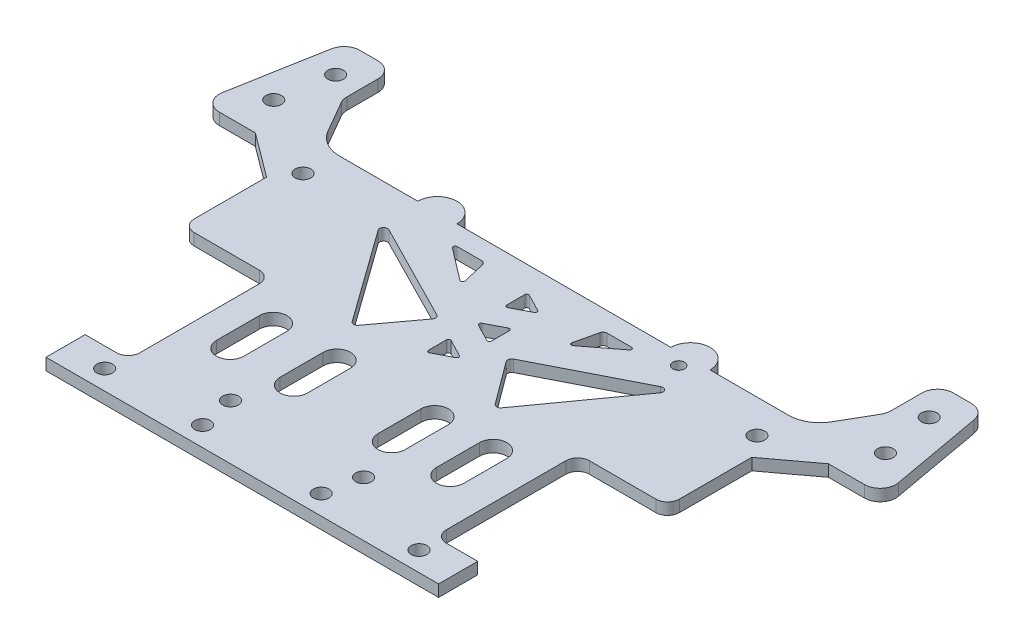
SolidWorks part; units mm, degrees
ref_plane "前视基准面" through (0, 0, 0) normal (0, 0, 1) x (1, 0, 0)
ref_plane "上视基准面" through (0, 0, 0) normal (0, 1, 0) x (1, 0, 0)
ref_plane "右视基准面" through (0, 0, 0) normal (1, 0, 0) x (0, 0, -1)
other "Configuration Table"
sketch "草图1" plane through (0, 0, 0) normal (0, 1, 0) x (1, 0, 0)
  line L0 (0, -104.2546) -> (0, 104.2546) construction
  point P3 (0, 0)
sketch "草图2" plane through (0, 0, 0) normal (0, 1, 0) x (1, 0, 0)
  line L0 (335.3431, 5) -> (-235.3431, 5) construction
  line L1 (-50, 0) -> (50, 0)
  line L2 (0, 0) -> (0, 19.5248) construction
  line L3 (42, 10) -> (50, 10)
  line L4 (50, 0) -> (50, 10)
  line L6 (0, 19.5248) -> (0, 40.19) construction
  line L8 (39, 13) -> (39, 43.53)
  line L9 (42, 46.53) -> (59, 46.53)
  line L10 (0, 40.19) -> (0, 82.03) construction
  line L11 (-57.3812, 82.03) -> (-37.34, 82.03)
  line L12 (62, 49.53) -> (62, 68.03)
  line L13 (64.3094, 86.03) -> (68.9641, 94.0922)
  line L14 (69.5, 96.0922) -> (69.5, 104.0204)
  line L17 (73.5, 108.0204) -> (78.1587, 108.0204)
  line L19 (82.0948, 104.7324) -> (86.3672, 81.1158)
  line L20 (62, 68.03) -> (73.2197, 76.4037)
  line L21 (73.2197, 76.4037) -> (82.4311, 76.4037)
  line L22 (12.5, 25.5) -> (12.5, 36.5) construction
  line L23 (9, 25.5) -> (9, 36.5)
  line L24 (16, 25.5) -> (16, 36.5)
  line L25 (-73.5, 108.0204) -> (-78.1587, 108.0204)
  line L26 (-69.5, 96.0922) -> (-69.5, 104.0204)
  line L27 (-64.3094, 86.03) -> (-68.9641, 94.0922)
  line L29 (-42.32, 10) -> (-50.32, 10)
  line L30 (-39.32, 13) -> (-39.32, 43.53)
  line L31 (-42.32, 46.53) -> (-59, 46.53)
  line L32 (-62, 49.53) -> (-62, 68.03)
  line L33 (-62, 68.03) -> (-73.2197, 76.4037)
  line L34 (-73.2197, 76.4037) -> (-82.4311, 76.4037)
  line L35 (-82.0948, 104.7324) -> (-86.3672, 81.1158)
  line L36 (-12.5, 25.5) -> (-12.5, 36.5) construction
  line L37 (-9, 25.5) -> (-9, 36.5)
  line L38 (-16, 25.5) -> (-16, 36.5)
  line L39 (-50.32, 10) -> (-50.32, 0)
  line L40 (-50, 0) -> (-50.32, 0)
  line L41 (-28.772, 36.5) -> (-28.772, 25.5) construction
  line L42 (-25.272, 36.5) -> (-25.272, 25.5)
  line L43 (-32.272, 36.5) -> (-32.272, 25.5)
  line L45 (27.4578, 36.5) -> (27.4578, 25.5) construction
  line L46 (30.9578, 36.5) -> (30.9578, 25.5)
  line L47 (23.9578, 36.5) -> (23.9578, 25.5)
  line L60 (-34.7339, 72.03) -> (-9.7834, 59.3228)
  line L61 (-9.4337, 57.8365) -> (-17.4687, 46.9881)
  line L62 (-19.0845, 47) -> (-36, 70.5556)
  line L63 (-22.2986, 77.03) -> (-15.9986, 77.03)
  line L64 (-15.0247, 76.2572) -> (-13.6616, 70.4141)
  line L65 (-14.4522, 69.9032) -> (-22.6022, 76.1328)
  line L66 (9.4337, 57.8365) -> (17.4687, 46.9881)
  line L67 (19.0845, 47) -> (36, 70.5556)
  line L68 (34.7339, 72.03) -> (9.7834, 59.3228)
  line L69 (14.4522, 69.9032) -> (22.6022, 76.1328)
  line L70 (15.0247, 76.2572) -> (13.6616, 70.4141)
  line L71 (22.2986, 77.03) -> (15.9986, 77.03)
  line L72 (-3.0133, 75.03) -> (-3.0133, 70.43)
  line L73 (-2.2833, 69.986) -> (2.1563, 72.286)
  line L74 (2.1563, 73.174) -> (-2.2833, 75.474)
  line L75 (3.0133, 65.0858) -> (3.0133, 60.4858)
  line L76 (2.2833, 60.0419) -> (-2.1563, 62.3419)
  line L77 (-2.1563, 63.2298) -> (2.2833, 65.5298)
  line L81 (-2.2833, 49.986) -> (2.1563, 52.286)
  line L82 (-3.0133, 55.03) -> (-3.0133, 50.43)
  line L83 (2.1563, 53.174) -> (-2.2833, 55.474)
  line L84 (32.34, 79) -> (32.34, 82.03) construction
  line L87 (-27.34, 82.03) -> (27.34, 82.03)
  line L88 (37.34, 82.03) -> (57.3812, 82.03)
  arc A0 (82.4311, 76.4037) -> (86.3672, 81.1158) centre (82.4311, 80.4037) ccw
  arc A1 (82.0948, 104.7324) -> (78.1587, 108.0204) centre (78.1587, 104.0204) ccw
  arc A2 (69.5, 104.0204) -> (73.5, 108.0204) centre (73.5, 104.0204) cw
  arc A3 (68.9641, 94.0922) -> (69.5, 96.0922) centre (65.5, 96.0922) ccw
  arc A4 (64.3094, 86.03) -> (57.3812, 82.03) centre (57.3812, 90.03) cw
  circle A5 centre (40, 5) radius 2
  circle A6 centre (15, 5) radius 2
  circle A7 centre (57.84, 73.5) radius 2
  circle A8 centre (16.84, 14) radius 2
  arc A9 (9, 25.5) -> (16, 25.5) centre (12.5, 25.5) ccw
  arc A10 (16, 36.5) -> (9, 36.5) centre (12.5, 36.5) ccw
  circle A11 centre (78.1587, 86.03) radius 2
  circle A12 centre (75.8293, 99.5272) radius 2
  arc A13 (-69.5, 104.0204) -> (-73.5, 108.0204) centre (-73.5, 104.0204) ccw
  arc A14 (-68.9641, 94.0922) -> (-69.5, 96.0922) centre (-65.5, 96.0922) cw
  arc A15 (-64.3094, 86.03) -> (-57.3812, 82.03) centre (-57.3812, 90.03) ccw
  arc A16 (-82.4311, 76.4037) -> (-86.3672, 81.1158) centre (-82.4311, 80.4037) cw
  arc A17 (-82.0948, 104.7324) -> (-78.1587, 108.0204) centre (-78.1587, 104.0204) cw
  circle A18 centre (-75.8293, 99.5272) radius 2
  circle A19 centre (-78.1587, 86.03) radius 2
  circle A20 centre (-58.16, 73.5) radius 2
  circle A21 centre (-40.32, 5) radius 2
  circle A22 centre (-15.32, 5) radius 2
  arc A24 (-9, 25.5) -> (-16, 25.5) centre (-12.5, 25.5) cw
  arc A25 (-16, 36.5) -> (-9, 36.5) centre (-12.5, 36.5) cw
  circle A26 centre (-17.16, 14) radius 2
  arc A27 (-59, 46.53) -> (-62, 49.53) centre (-59, 49.53) cw
  arc A28 (-39.32, 13) -> (-42.32, 10) centre (-42.32, 13) cw
  arc A29 (-42.32, 46.53) -> (-39.32, 43.53) centre (-42.32, 43.53) cw
  arc A30 (39, 43.53) -> (42, 46.53) centre (42, 43.53) cw
  arc A31 (59, 46.53) -> (62, 49.53) centre (59, 49.53) ccw
  arc A32 (42, 10) -> (39, 13) centre (42, 13) cw
  arc A33 (-25.272, 36.5) -> (-32.272, 36.5) centre (-28.772, 36.5) ccw
  arc A34 (-32.272, 25.5) -> (-25.272, 25.5) centre (-28.772, 25.5) ccw
  arc A35 (30.9578, 36.5) -> (23.9578, 36.5) centre (27.4578, 36.5) ccw
  arc A36 (23.9578, 25.5) -> (30.9578, 25.5) centre (27.4578, 25.5) ccw
  arc A37 (-34.7339, 72.03) -> (-36, 70.5556) centre (-35.1877, 71.1389) ccw
  arc A38 (-9.7834, 59.3228) -> (-9.4337, 57.8365) centre (-10.2372, 58.4317) cw
  arc A39 (-17.4687, 46.9881) -> (-19.0845, 47) centre (-18.2723, 47.5833) cw
  arc A40 (-15.9986, 77.03) -> (-15.0247, 76.2572) centre (-15.9986, 76.03) cw
  arc A41 (-22.2986, 77.03) -> (-22.6022, 76.1328) centre (-22.2986, 76.53) ccw
  arc A42 (-13.6616, 70.4141) -> (-14.4522, 69.9032) centre (-14.1486, 70.3005) cw
  arc A43 (9.7834, 59.3228) -> (9.4337, 57.8365) centre (10.2372, 58.4317) ccw
  arc A44 (17.4687, 46.9881) -> (19.0845, 47) centre (18.2723, 47.5833) ccw
  arc A45 (34.7339, 72.03) -> (36, 70.5556) centre (35.1877, 71.1389) cw
  arc A46 (22.2986, 77.03) -> (22.6022, 76.1328) centre (22.2986, 76.53) cw
  arc A47 (13.6616, 70.4141) -> (14.4522, 69.9032) centre (14.1486, 70.3005) ccw
  arc A48 (15.9986, 77.03) -> (15.0247, 76.2572) centre (15.9986, 76.03) ccw
  arc A49 (2.1563, 52.286) -> (2.1563, 53.174) centre (1.9263, 52.73) ccw
  arc A50 (-2.2833, 49.986) -> (-3.0133, 50.43) centre (-2.5133, 50.43) cw
  arc A51 (-3.0133, 55.03) -> (-2.2833, 55.474) centre (-2.5133, 55.03) cw
  arc A52 (3.0133, 60.4858) -> (2.2833, 60.0419) centre (2.5133, 60.4858) cw
  arc A53 (3.0133, 65.0858) -> (2.2833, 65.5298) centre (2.5133, 65.0858) ccw
  arc A54 (-2.1563, 62.3419) -> (-2.1563, 63.2298) centre (-1.9263, 62.7858) cw
  arc A55 (2.1563, 72.286) -> (2.1563, 73.174) centre (1.9263, 72.73) ccw
  arc A56 (-3.0133, 70.43) -> (-2.2833, 69.986) centre (-2.5133, 70.43) ccw
  arc A57 (-3.0133, 75.03) -> (-2.2833, 75.474) centre (-2.5133, 75.03) cw
  circle A58 centre (32.34, 79) radius 1.5
  arc A59 (27.34, 82.03) -> (37.34, 82.03) centre (32.34, 82.03) cw
  arc A60 (-27.34, 82.03) -> (-37.34, 82.03) centre (-32.34, 82.03) ccw
  point P11 (62, 68.03)
  point P14 (50, 5)
  point P29 (87.2197, 76.4037)
  point P33 (81.5, 108.0204)
  point P36 (69.5, 108.0204)
  point P39 (69.5, 95.0204)
  point P42 (62, 82.03)
  point P44 (12.5, 31)
  point P51 (12.5, 40)
  point P52 (12.5, 22)
  point P57 (-46.32, 10)
  point P58 (-69.5, 100.0563)
  point P64 (75.8293, 108.0204)
  point P79 (-39.32, 10)
  point P101 (-12.5, 31)
  point P111 (39, 46.53)
  point P114 (62, 46.53)
  point P117 (39, 10)
  point P120 (-28.772, 31)
  point P127 (27.4578, 31)
  point P178 (-3.0133, 72.73)
  point P180 (3.0133, 62.7858)
  point P195 (-3.0133, 62.7858)
  point P198 (3.0133, 72.73)
  dimension "D15" = 4
  dimension "D16" = 4
  dimension "D17" = 4
  dimension "D18" = 8
  dimension "D19" = 4
  dimension "D20" = 4
  dimension "D25" = 4
  dimension "D26" = 4
  dimension "D31" = 40
  dimension "D33" = 4
  dimension "D34" = 4
  dimension "D35" = 6.3293
  dimension "D36" = 8.4931
  dimension "D39" = 4
  dimension "D42" = 22.16
  dimension "D47" = 116
  dimension "D48" = 59.5
  dimension "D49" = 4
  dimension "D50" = 5
  dimension "D51" = 4
  dimension "D52" = 35
  dimension "D53" = 5
  dimension "D54" = 10
  dimension "D55" = 4
  dimension "D24" = 59.5
  dimension "D23" = 41
  dimension "D56" = 14
  dimension "D61" = 4
  dimension "D62" = 4
  dimension "D63" = 4
  dimension "D64" = 24
  dimension "D65" = 2.9037
  dimension "D66" = 9.6263
  dimension "D70" = 8
  dimension "D71" = 4
  dimension "D58" = 4
  dimension "D72" = 4
  dimension "D74" = 8.4931
  dimension "D67" = 8.6587
  dimension "D73" = 6.3293
  dimension "D75" = 3
  dimension "D76" = 3
  dimension "D77" = 3
  dimension "D80" = 11.5
  dimension "D81" = 22.5
  dimension "D85" = 25.5
  dimension "D86" = 1
  dimension "D87" = 1
  dimension "D88" = 1
  dimension "D89" = 1
  dimension "D90" = 0.5
  dimension "D91" = 0.5
  dimension "D92" = 0.5
  dimension "D109" = 3
  dimension "D112" = 5
  dimension "D1" = 50
  dimension "D2" = 10
  dimension "D3" = 36.53
  dimension "D4" = 39
  dimension "D5" = 62
  dimension "D6" = 35.5
  dimension "D7" = 14
  dimension "D8" = 15
  dimension "D9" = 14
  dimension "D10" = 14
  dimension "D11" = 60
  dimension "D12" = 15
  dimension "D13" = 13
  dimension "D14" = 12
  dimension "D21" = 10
  dimension "D22" = 24
  dimension "D27" = 4
  dimension "D28" = 22.16
  dimension "D29" = 30
  dimension "D30" = 23
  dimension "D32" = 22
  dimension "D37" = 9.6263
  dimension "D38" = 8.6587
  dimension "D40" = 34
  dimension "D41" = 14
  dimension "D43" = 36.53
  dimension "D44" = 124
  dimension "D45" = 11
  dimension "D46" = 10
  dimension "D57" = 9.2114
  dimension "D59" = 4.6587
  dimension "D60" = 7.9282
  dimension "D68" = 60
  dimension "D69" = 9.3094
  dimension "D78" = 25
  dimension "D79" = 8.16
  dimension "D82" = 31
  dimension "D83" = 8.0422
  dimension "D84" = 14.048
  dimension "D93" = 6.3
  dimension "D94" = 8.15
  dimension "D95" = 13.6616
  dimension "D96" = 5
  dimension "D97" = 10.2581
  dimension "D98" = 29
  dimension "D99" = 28
  dimension "D100" = 13.5
  dimension "D101" = 10
  dimension "D102" = 26
  dimension "D103" = 47
  dimension "D104" = 4.6
  dimension "D105" = 5
  dimension "D106" = 7
  dimension "D107" = 18.8002
  dimension "D108" = 27
  dimension "D110" = 25.5
  dimension "D111" = 5.5
extrude "凸台-拉伸2" add sketch "草图2" along normal blind 3
